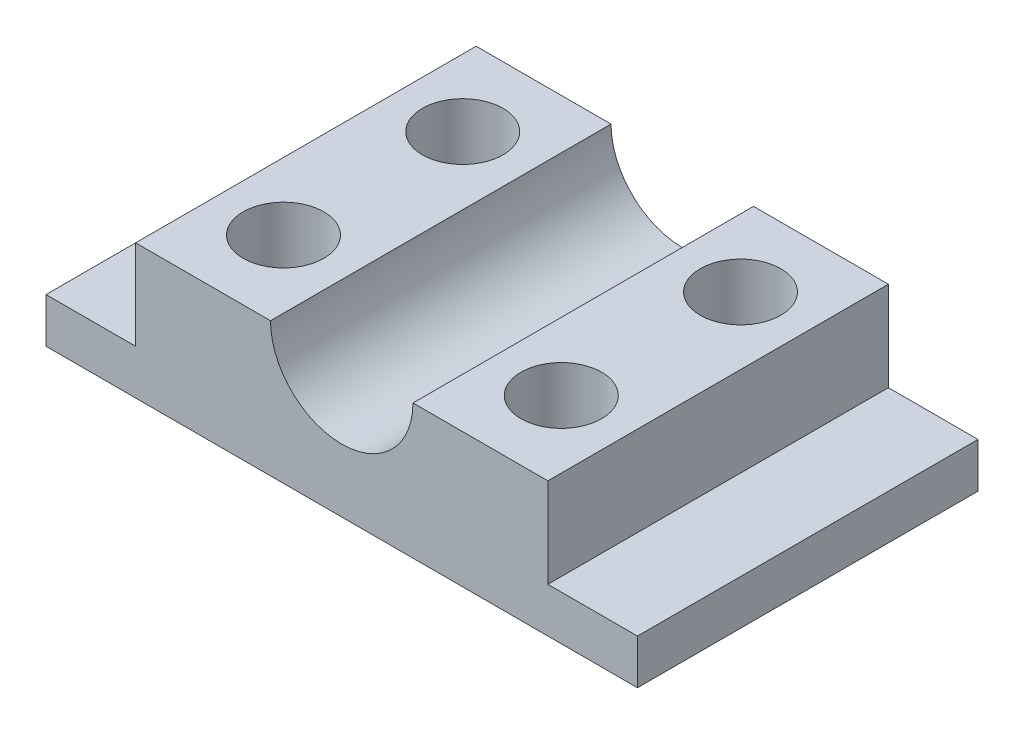
SolidWorks part; units mm, degrees
ref_plane "Front Plane" through (0, 0, 0) normal (0, 0, 1) x (1, 0, 0)
ref_plane "Top Plane" through (0, 0, 0) normal (0, 1, 0) x (1, 0, 0)
ref_plane "Right Plane" through (0, 0, 0) normal (1, 0, 0) x (0, 0, -1)
sketch "Sketch1" plane through (0, 0, 0) normal (0, 1, 0) x (1, 0, 0)
  line L1 (0, 0) -> (46, 0)
  line L2 (0, 0) -> (0, 38)
  line L3 (0, 38) -> (46, 38)
  line L4 (46, 0) -> (46, 38)
  dimension "D1" = 46
  dimension "D2" = 38
extrude "Boss-Extrude1" add sketch "Sketch1" along normal blind 15
ref_plane "Plane4" through (23, 0, 0) normal (1, 0, 0) x (0, 0, -1)
sketch "Sketch4" plane through (0, 15, 0) normal (0, 1, 0) x (1, 0, 0)
  line L0 (0, 38) -> (0, 0) construction
  line L1 (7.5, 29) -> (38.5, 29)
  line L2 (7.5, 29) -> (7.5, 9)
  line L3 (7.5, 9) -> (38.5, 9)
  line L4 (38.5, 29) -> (38.5, 9)
  line L7 (46, 0) -> (46, 38) construction
  line L8 (0, 0) -> (46, 0) construction
  line L9 (13.2102, 9) -> (13.2102, 0) construction
  line L10 (13.2102, 38) -> (13.2102, 29) construction
  line L11 (46, 38) -> (0, 38) construction
  dimension "D1" = 7.5
  dimension "D2" = 20
  dimension "D4" = 7.5
hole_wizard "M10x1.0 Tapped Hole1" positions "Sketch5" profile "Sketch6" tap size "M10x1.0" standard "ANSI Metric" end condition through all
sketch "Sketch5" plane through (0, 15, 0) normal (0, 1, 0) x (1, 0, 0)
  point P0 (7.5, 29)
  point P3 (38.5, 29)
  point P6 (38.5, 9)
  point P9 (7.5, 9)
sketch "Sketch6" plane through (7.5, 15, -29) normal (1, 0, 0) x (0, 0, 1)
  line L0 (0, 0) -> (0, 15)
  line L1 (0, 15) -> (4.5, 15)
  line L2 (4.5, 15) -> (4.5, 0)
  line L5 (4.5, 0) -> (0, 0)
  line L11 (0, -6.35) -> (0, 107.95) construction
  dimension "Thru Tap Drill Dia." = 9
  dimension "Thru Tap Drill Depth" = 15
sketch "Sketch7" plane through (0, 0, 0) normal (0, 0, 1) x (1, 0, 0)
  line L0 (0, 15) -> (46, 15) construction
  circle A0 centre (23, 15) radius 7.95
  dimension "D2" = 15.9
extrude "Cut-Extrude1" cut sketch "Sketch7" against normal through all
sketch "Sketch17" plane through (46, 0, 0) normal (1, 0, 0) x (0, 0, -1)
  line L0 (38, 15) -> (38, 0) construction
  line L1 (0, 0) -> (38, 0)
  line L2 (0, 0) -> (0, 5)
  line L3 (0, 5) -> (38, 5)
  line L4 (38, 0) -> (38, 5)
  dimension "D1" = 5
extrude "Boss-Extrude2" add sketch "Sketch17" along normal blind 10
sketch "Sketch18" plane through (0, 0, 0) normal (-1, 0, 0) x (0, 0, 1)
  line L0 (0, 15) -> (0, 0) construction
  line L1 (-38, 0) -> (0, 0)
  line L2 (-38, 0) -> (-38, 5)
  line L3 (-38, 5) -> (0, 5)
  line L4 (0, 0) -> (0, 5)
  dimension "D1" = 5
extrude "Boss-Extrude3" add sketch "Sketch18" along normal blind 10
sketch "Sketch19" plane through (0, 5, 0) normal (0, 1, 0) x (1, 0, 0)
  line L0 (51, 38) -> (51, 0) construction
  line L1 (56, 38) -> (46, 38) construction
  line L2 (56, 0) -> (46, 0) construction
  line L3 (51, 38) -> (51, 29)
  line L4 (51, 0) -> (51, 9)
  line L5 (-5, 0) -> (-5, 38) construction
  line L6 (-10, 0) -> (0, 0) construction
  line L7 (-10, 38) -> (0, 38) construction
  line L8 (-5, 38) -> (-5, 29)
  line L9 (-5, 0) -> (-5, 9)
  dimension "D1" = 9
  dimension "D2" = 9
  dimension "D3" = 9
  dimension "D4" = 9
hole_wizard "Ø5.0mm Dowel Hole1" [suppressed] positions "Sketch20" profile "Sketch21" hole size "Ø5.0" standard "ANSI Metric"
sketch "Sketch20" plane through (0, 5, 0) normal (0, 1, 0) x (1, 0, 0)
  point P0 (-5, 9)
  point P3 (-5, 29)
  point P6 (51, 9)
  point P9 (51, 29)
sketch "Sketch21" plane through (-5, 5, -9) normal (1, 0, 0) x (0, 0, 1)
  line L0 (0, 0) -> (0, 5)
  line L1 (0, 5) -> (2.5, 5)
  line L2 (2.5, 5) -> (2.5, 0)
  line L5 (2.5, 0) -> (0, 0)
  line L11 (0, -6.35) -> (0, 107.95) construction
  dimension "Thru Hole Dia." = 5
  dimension "Thru Hole Depth" = 5
ref_plane "Plane5" through (0, 5, 0) normal (0, 0, -1) x (-1, 0, 0)
ref_plane "Plane6" through (0, 0, -19) normal (0, 0, 1) x (1, 0, 0)
sketch "Sketch23" plane through (0, 0, -19) normal (0, 0, 1) x (1, 0, 0)
  line L6 (-10, 5) -> (0, 15) construction
  line L7 (0, 15) -> (0, 5) construction
  line L9 (0, 5) -> (-10, 5) construction
  line L10 (0, 15) -> (0, 5)
  line L11 (0, 5) -> (0, 15)
  line L12 (-10, 5) -> (0, 15)
  line L13 (-10, 5) -> (0, 5)
fillet "Fillet1" [suppressed] radius 10
